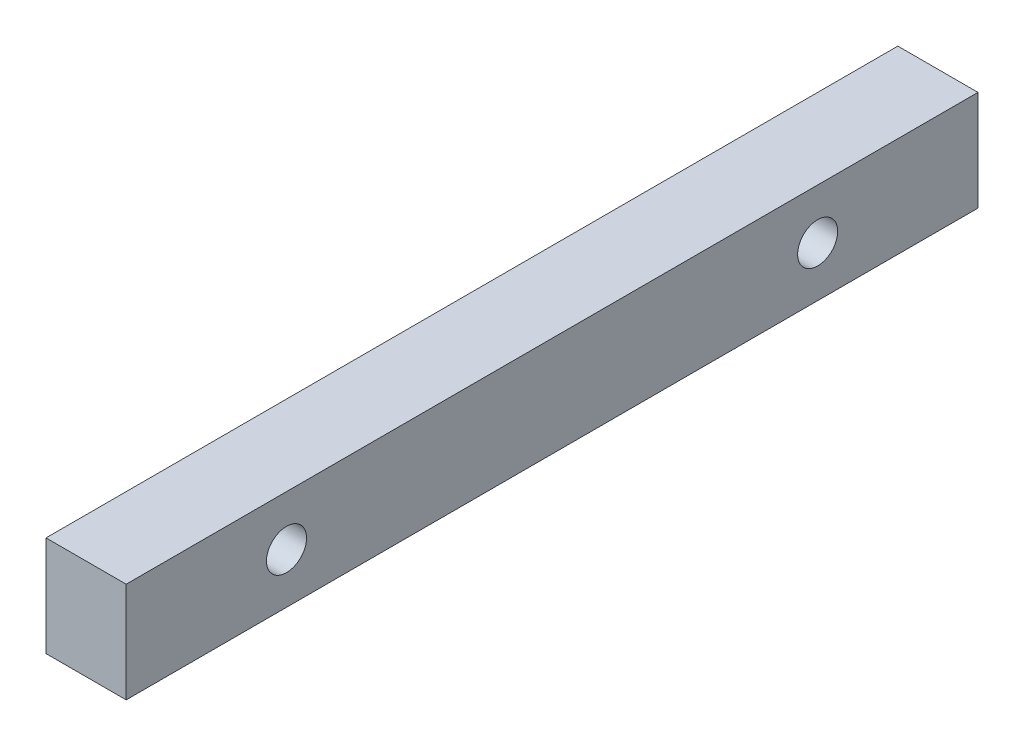
SolidWorks part; units mm, degrees
ref_plane "前视基准面" through (0, 0, 0) normal (0, 0, 1) x (1, 0, 0)
ref_plane "上视基准面" through (0, 0, 0) normal (0, 1, 0) x (1, 0, 0)
ref_plane "右视基准面" through (0, 0, 0) normal (1, 0, 0) x (0, 0, -1)
sketch "草图1" plane through (0, 0, 0) normal (0, 0, 1) x (1, 0, 0)
  line L1 (-10, -20) -> (30, -20)
  line L2 (-10, -20) -> (-10, 30)
  line L3 (-10, 30) -> (30, 30)
  line L4 (30, -20) -> (30, 30)
  line L5 (-10, -20) -> (30, 30) construction
  line L6 (-10, 30) -> (30, -20) construction
  dimension "D2" = 40
  dimension "D3" = 50
extrude "凸台-拉伸1" add sketch "草图1" along normal mid plane 425
sketch "草图2" plane through (30, 0, 0) normal (1, 0, 0) x (0, 0, -1)
  line L0 (-212.5, 30) -> (212.5, 30) construction
  circle A0 centre (-132.5, 5) radius 10
  circle A1 centre (132.5, 5) radius 10
  dimension "D1" = 132.5
  dimension "D3" = 20
  dimension "D4" = 20
  dimension "D2" = 132.5
  dimension "D5" = 25
  dimension "D6" = 25
extrude "切除-拉伸1" cut sketch "草图2" against normal up to next
